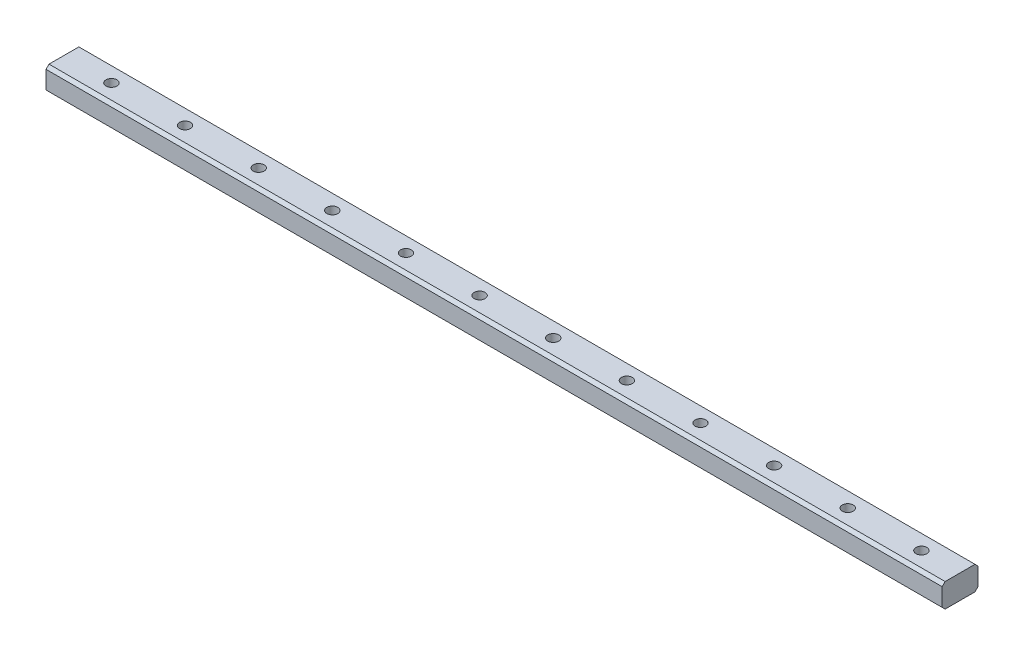
SolidWorks part; units mm, degrees
ref_plane "Front Plane" through (0, 0, 0) normal (0, 0, 1) x (1, 0, 0)
ref_plane "Top Plane" through (0, 0, 0) normal (0, 1, 0) x (1, 0, 0)
ref_plane "Right Plane" through (0, 0, 0) normal (1, 0, 0) x (0, 0, -1)
sketch "Sketch1" plane through (0, 0, 0) normal (0, 1, 0) x (1, 0, 0)
  line L1 (150, -6) -> (-150, -6)
  line L2 (150, -6) -> (150, 6)
  line L3 (150, 6) -> (-150, 6)
  line L4 (-150, -6) -> (-150, 6)
  line L5 (150, -6) -> (-150, 6) construction
  line L6 (150, 6) -> (-150, -6) construction
  point P0 (0, 0)
  dimension "D1" = 300
  dimension "D2" = 12
extrude "Boss-Extrude1" add sketch "Sketch1" along normal blind 8
chamfer "Chamfer1" distance 1 angle 45 4 edges at (0, 0, -6) (0, 0, 6) (0, 8, 6) (0, 8, -6)
sketch "Sketch2" plane through (0, 0, 0) normal (0, 1, 0) x (1, 0, 0)
  line L0 (-4.4, 0) -> (4.4, 0) construction
  line L1 (150, -5) -> (150, 5) construction
  circle A0 centre (137.05, 0) radius 2.95
  dimension "D1" = 5.9
  dimension "D2" = 12.95
extrude "Cut-Extrude1" cut sketch "Sketch2" along normal blind 5.05
sketch "Sketch3" plane through (0, 0, 0) normal (0, 1, 0) x (1, 0, 0)
  circle A0 centre (137.05, 0) radius 1.825
  dimension "D1" = 3.65
extrude "Cut-Extrude2" cut sketch "Sketch3" along normal through all
pattern_linear "LPattern2" count 12 spacing 24.65 along (-1, 0, 0) of "Cut-Extrude1", "Cut-Extrude2"
